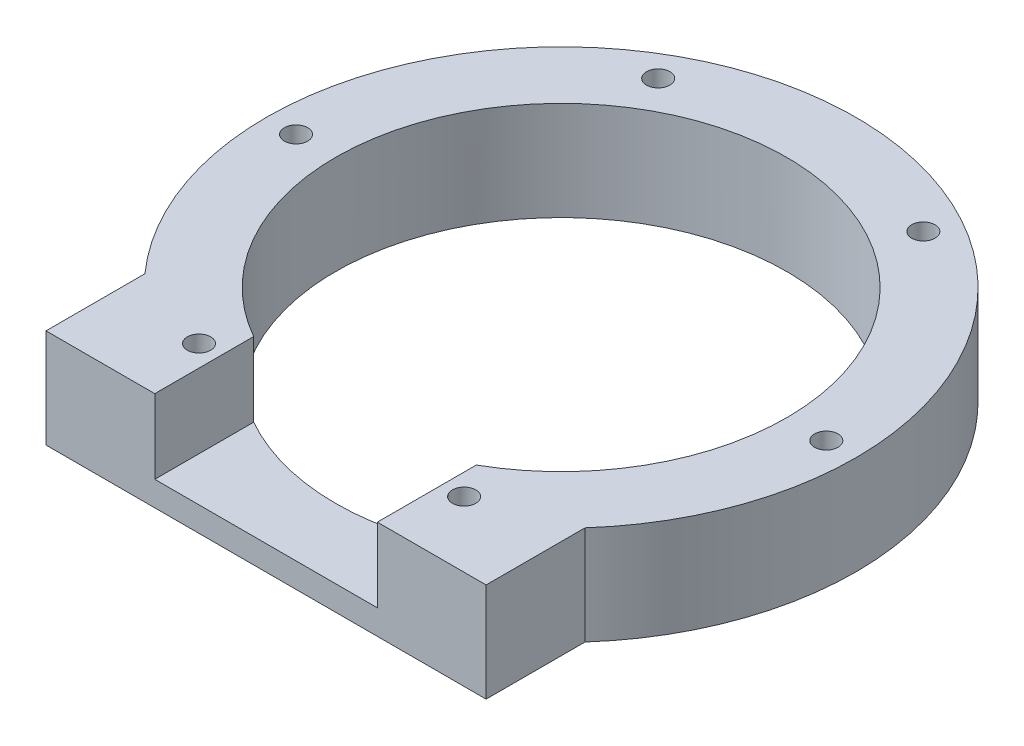
SolidWorks part; units mm, degrees
ref_plane "Front Plane" through (0, 0, 0) normal (0, 0, 1) x (1, 0, 0)
ref_plane "Top Plane" through (0, 0, 0) normal (0, 1, 0) x (1, 0, 0)
ref_plane "Right Plane" through (0, 0, 0) normal (1, 0, 0) x (0, 0, -1)
sketch "Sketch1" plane through (0, 0, 0) normal (0, 1, 0) x (1, 0, 0)
  line L0 (34.036, 0) -> (37.846, 0) construction
  line L1 (34.036, 0) -> (28.956, 0) construction
  line L2 (-14.2875, -25.1857) -> (14.2875, -25.1857) construction
  line L3 (14.2875, -25.1857) -> (28.2489, -25.1857)
  line L4 (-14.2875, -25.1857) -> (-28.2489, -25.1857)
  circle A0 centre (0, 0) radius 34.036 construction
  circle A1 centre (0, 0) radius 37.846
  circle A2 centre (0, 0) radius 28.956
  point P3 (34.036, 0)
  point P4 (17.018, -29.476)
  point P7 (-17.018, -29.476)
  point P8 (-34.036, 0)
  point P9 (-17.018, 29.476)
  point P10 (17.018, 29.476)
  dimension "D1" = 68.072
  dimension "D3" = 3.81
  dimension "D4" = 28.575
  dimension "D5" = 5.08
  dimension "D2" = 6
extrude "Boss-Extrude1" add sketch "Sketch1" along normal blind 12.7
sketch "Sketch5" plane through (0, 0, 25.1857) normal (0, 0, 1) x (1, 0, 0)
  line L0 (37.846, 0) -> (-37.846, 0) construction
  line L1 (-28.2489, 12.7) -> (-14.2875, 12.7)
  line L2 (-28.2489, 12.7) -> (-28.2489, 0)
  line L3 (-28.2489, 0) -> (-14.2875, 0)
  line L4 (-14.2875, 12.7) -> (-14.2875, 0)
  line L5 (-14.2875, 12.7) -> (-14.2875, 0) construction
  line L7 (28.2489, 0) -> (14.2875, 0)
  line L8 (28.2489, 0) -> (28.2489, 12.7)
  line L9 (28.2489, 12.7) -> (14.2875, 12.7)
  line L10 (14.2875, 0) -> (14.2875, 12.7)
extrude "Boss-Extrude3" add sketch "Sketch5" along normal blind 12.7
hole_wizard "Ø3.0mm Dowel Hole1" positions "Sketch8" profile "Sketch10" hole size "Ø3.0" standard "ANSI Metric" end condition through all
sketch "Sketch8" plane through (0, 0, 0) normal (0, -1, 0) x (-1, 0, 0)
  point P0 (-17.018, 29.476)
  point P3 (-34.036, 0)
  point P6 (17.018, 29.476)
  point P9 (34.036, 0)
  point P12 (17.018, -29.476)
  point P15 (-17.018, -29.476)
sketch "Sketch10" plane through (17.018, 0, -29.476) normal (1, 0, 0) x (0, 0, -1)
  line L0 (0, 0) -> (0, 12.7)
  line L1 (0, 12.7) -> (1.5, 12.7)
  line L2 (1.5, 12.7) -> (1.5, 0)
  line L5 (1.5, 0) -> (0, 0)
  line L11 (0, -6.35) -> (0, 107.95) construction
  dimension "Thru Hole Dia." = 3
  dimension "Thru Hole Depth" = 12.7
sketch "Sketch11" plane through (0, 0, 0) normal (0, -1, 0) x (1, 0, 0)
  line L1 (-14.2875, 25.1857) -> (14.2875, 25.1857)
  line L2 (-14.2875, 25.1857) -> (-14.2875, 37.8857)
  line L3 (-14.2875, 37.8857) -> (14.2875, 37.8857)
  line L4 (14.2875, 25.1857) -> (14.2875, 37.8857)
  arc A0 (-14.2875, 25.1857) -> (14.2875, 25.1857) centre (0, 0) cw
  circle A1 centre (0, 0) radius 28.956 construction
  line M12 (-14.2875, 25.1857) -> (-14.2875, 37.8857)
  line M18 (14.2875, 37.8857) -> (14.2875, 25.1857)
extrude "Boss-Extrude4" add sketch "Sketch11" against normal blind 3.175 contours A0 L3 M12 M18
sketch "Sketch13" plane through (0, 0, 0) normal (0, -1, 0) x (1, 0, 0)
  line L0 (6.985, 0) -> (-6.985, 0) construction
  line L1 (30.5146, 0) -> (31.6053, 0) construction
  line L2 (30.5146, 0) -> (29.424, 0) construction
  line L3 (34.036, 0) -> (28.956, 0) construction
  circle A0 centre (-0.6004, 0) radius 31.115 construction
  circle A1 centre (0, 0) radius 31.6053 construction
  circle A2 centre (0, 0) radius 29.424 construction
  dimension "D1" = 62.23
sketch "Sketch14" plane through (0, 0, 0) normal (0, 1, 0) x (1, 0, 0)
  circle A0 centre (0, 0) radius 44.45
  circle A1 centre (0, 0) radius 37.846
  circle A2 centre (0, 0) radius 37.846 construction
  dimension "D1" = 88.9
